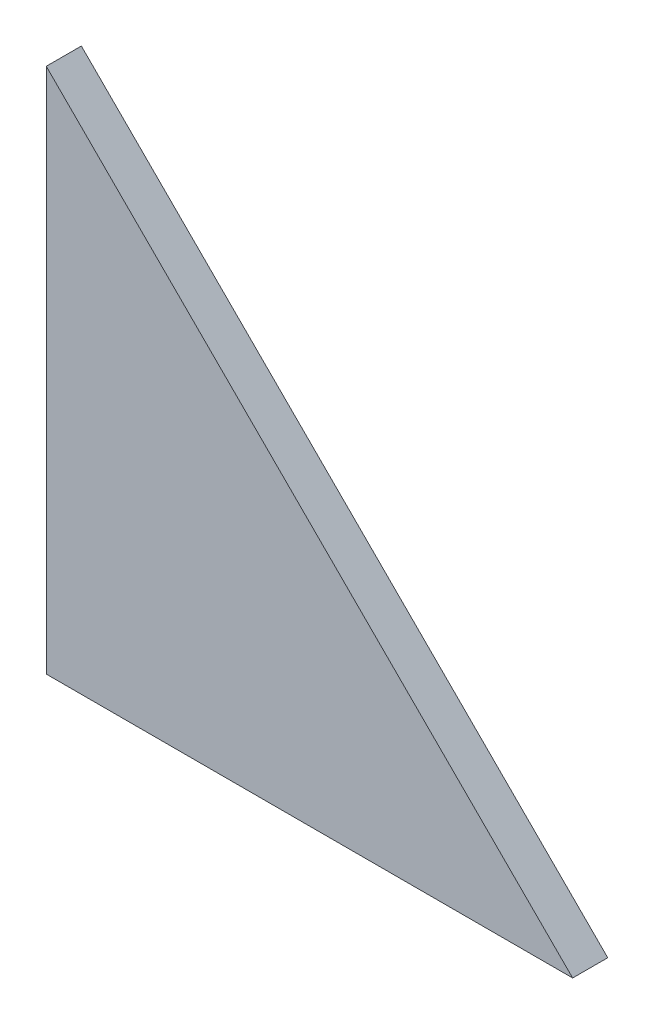
SolidWorks part; units mm, degrees
ref_plane "Alzado" through (0, 0, 0) normal (0, 0, 1) x (1, 0, 0)
ref_plane "Planta" through (0, 0, 0) normal (0, 1, 0) x (1, 0, 0)
ref_plane "Vista lateral" through (0, 0, 0) normal (1, 0, 0) x (0, 0, -1)
sketch "Croquis1" plane through (0, 0, 0) normal (0, 0, 1) x (1, 0, 0)
  line L0 (-26.1089, 126.7958) -> (-26.1089, -23.2042)
  line L1 (-26.1089, -23.2042) -> (123.8911, -23.2042)
  line L2 (123.8911, -23.2042) -> (-26.1089, 126.7958)
  dimension "D1" = 45
  dimension "D2" = 150
extrude "Saliente-Extruir1" add sketch "Croquis1" along normal blind 10
